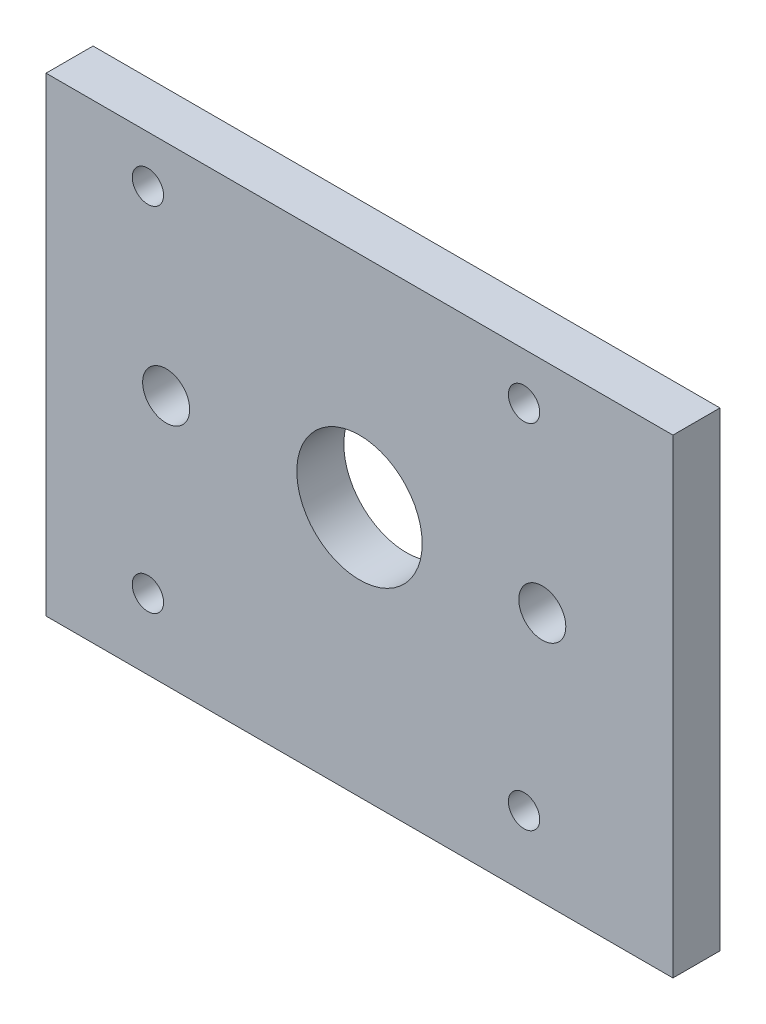
SolidWorks part; units mm, degrees
ref_plane "Front" through (0, 0, 0) normal (0, 0, 1) x (1, 0, 0)
ref_plane "Top" through (0, 0, 0) normal (0, 1, 0) x (1, 0, 0)
ref_plane "Right" through (0, 0, 0) normal (1, 0, 0) x (0, 0, -1)
sketch "草图1" plane through (0, 0, 0) normal (0, 0, 1) x (1, 0, 0)
  line L0 (40, 35) -> (40, -35) construction
  line L1 (-40, 35) -> (40, 35) construction
  line L2 (-40, -35) -> (-40, 35) construction
  line L3 (40, 35) -> (40, -25)
  line L4 (-40, 35) -> (40, 35)
  line L5 (-40, -25) -> (-40, 35)
  line L6 (-40, -25) -> (40, -25)
  circle A0 centre (23.3281, 7) radius 3 construction
  circle A1 centre (-24.6719, 7) radius 3 construction
  circle A2 centre (23.3281, 7) radius 3
  circle A3 centre (-24.6719, 7) radius 3
  circle A4 centre (-27, 29) radius 2
  circle A5 centre (21, 29) radius 2
  circle A6 centre (-27, -16) radius 2
  circle A7 centre (21, -16) radius 2
  circle A8 centre (0, 7) radius 8 construction
  circle A9 centre (0, 7) radius 8
  dimension "D1" = 4
  dimension "D2" = 60
  dimension "D3" = 13
  dimension "D4" = 9
  dimension "D5" = 45
  dimension "D6" = 48
extrude "凸台-拉伸1" add sketch "草图1" along normal blind 6
